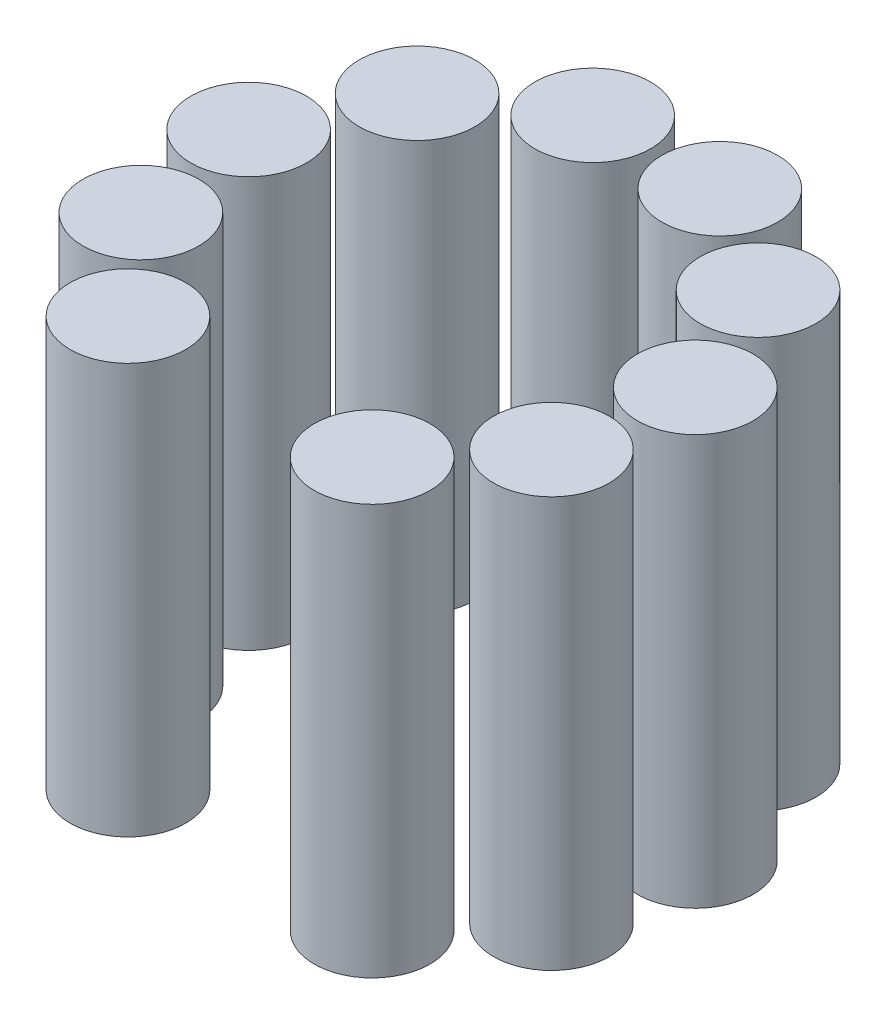
SolidWorks part; units mm, degrees
ref_plane "Front Plane" through (0, 0, 0) normal (0, 0, 1) x (1, 0, 0)
ref_plane "Top Plane" through (0, 0, 0) normal (0, 1, 0) x (1, 0, 0)
ref_plane "Right Plane" through (0, 0, 0) normal (1, 0, 0) x (0, 0, -1)
sketch "Sketch1" plane through (0, 0, 0) normal (0, 1, 0) x (1, 0, 0)
  line L0 (0, 0) -> (0, 35.75) construction
  line L1 (0, 0) -> (-10.0698, 34.3025) construction
  line L2 (0, 0) -> (-10.0698, 34.3025) construction
  line L3 (0, 0) -> (-27.0136, 23.4164) construction
  line L4 (0, -35.75) -> (0, 35.75) construction
  circle A0 centre (0, 0) radius 35.75 construction
  circle A1 centre (-10.0698, 34.3025) radius 9.175
  circle A2 centre (-27.0136, 23.4164) radius 9.175
  circle A3 centre (-35.3845, 5.099) radius 9.175
  circle A4 centre (-32.5259, -14.8366) radius 9.175
  circle A5 centre (-19.3451, -30.0638) radius 9.175
  circle A6 centre (19.3451, -30.0638) radius 9.175
  circle A7 centre (32.5259, -14.8366) radius 9.175
  circle A8 centre (35.3845, 5.099) radius 9.175
  circle A9 centre (27.0136, 23.4164) radius 9.175
  circle A10 centre (10.0698, 34.3025) radius 9.175
  dimension "D1" = 71.5
  dimension "D2" = 18.35
  dimension "D3" = 16.36
  dimension "D5" = 32.72
  dimension "D4" = 5
extrude "Boss-Extrude1" add sketch "Sketch1" along normal blind 65
